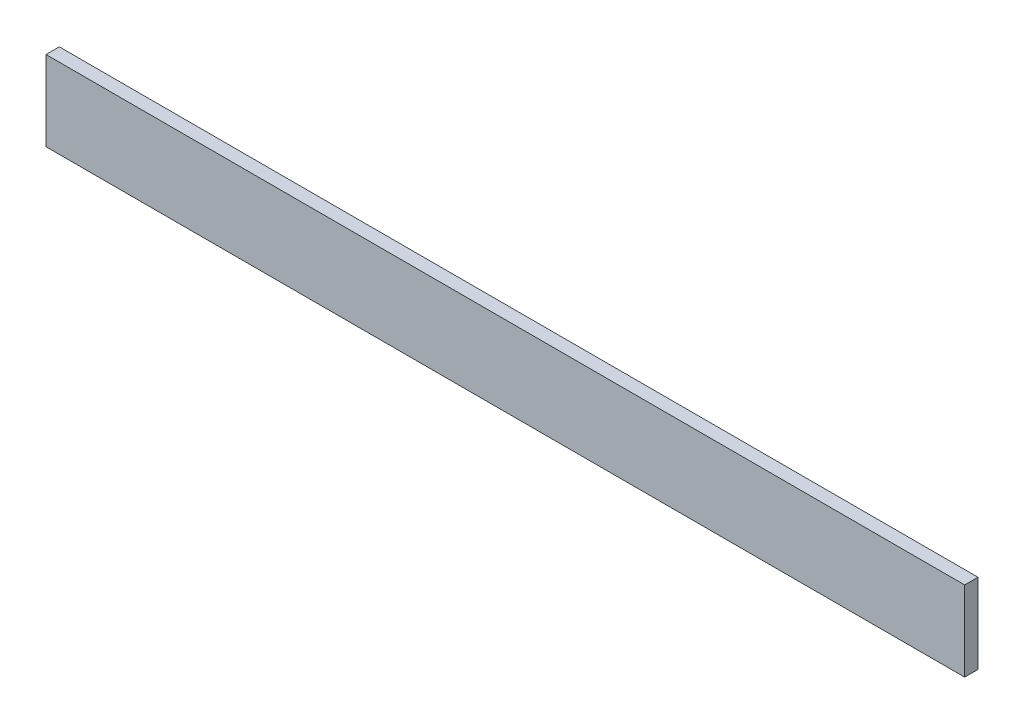
SolidWorks part; units mm, degrees
ref_plane "Front Plane" through (0, 0, 0) normal (0, 0, 1) x (1, 0, 0)
ref_plane "Top Plane" through (0, 0, 0) normal (0, 1, 0) x (1, 0, 0)
ref_plane "Right Plane" through (0, 0, 0) normal (1, 0, 0) x (0, 0, -1)
sketch "Sketch1" plane through (0, 0, 0) normal (1, 0, 0) x (0, 0, -1)
  line L1 (0, 0) -> (50.8, 0)
  line L2 (0, 0) -> (0, 304.8)
  line L3 (0, 304.8) -> (50.8, 304.8)
  line L4 (50.8, 0) -> (50.8, 304.8)
extrude "Boss-Extrude1" add sketch "Sketch1" along normal blind 3505.2
